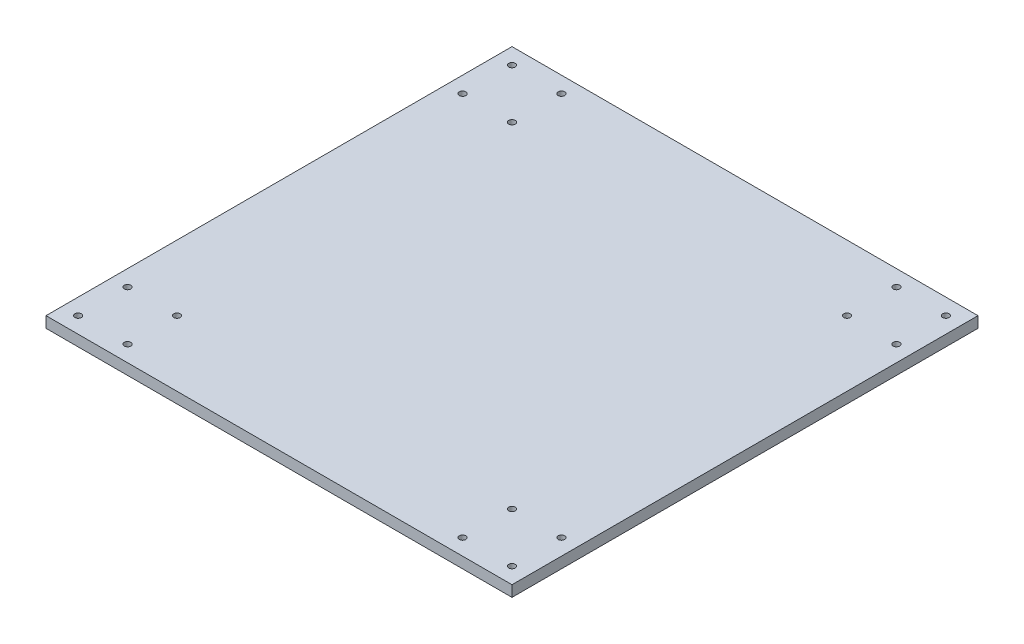
SolidWorks part; units mm, degrees
ref_plane "Front Plane" through (0, 0, 0) normal (0, 0, 1) x (1, 0, 0)
ref_plane "Top Plane" through (0, 0, 0) normal (0, 1, 0) x (1, 0, 0)
ref_plane "Right Plane" through (0, 0, 0) normal (1, 0, 0) x (0, 0, -1)
sketch "Sketch1" plane through (0, 0, 0) normal (0, 1, 0) x (1, 0, 0)
  line L0 (91.3003, -118.2497) -> (118.2497, -118.2497) construction
  line L1 (-127, -127) -> (127, -127)
  line L2 (-127, -127) -> (-127, 127)
  line L3 (-127, 127) -> (127, 127)
  line L4 (127, -127) -> (127, 127)
  line L5 (-127, -127) -> (127, 127) construction
  line L6 (-127, 127) -> (127, -127) construction
  line L7 (-104.775, 104.775) -> (104.775, 104.775) construction
  line L8 (-104.775, 104.775) -> (-104.775, -104.775) construction
  line L9 (-104.775, -104.775) -> (104.775, -104.775) construction
  line L10 (104.775, 104.775) -> (104.775, -104.775) construction
  line L11 (-104.775, 104.775) -> (104.775, -104.775) construction
  line L12 (-104.775, -104.775) -> (104.775, 104.775) construction
  line L13 (-118.2497, -118.2497) -> (-91.3003, -118.2497) construction
  line L14 (-118.2497, -118.2497) -> (-118.2497, -91.3003) construction
  line L15 (-118.2497, -91.3003) -> (-91.3003, -91.3003) construction
  line L16 (-91.3003, -118.2497) -> (-91.3003, -91.3003) construction
  line L17 (-118.2497, -118.2497) -> (-91.3003, -91.3003) construction
  line L18 (-118.2497, -91.3003) -> (-91.3003, -118.2497) construction
  line L19 (91.3003, -118.2497) -> (91.3003, -91.3003) construction
  line L20 (91.3003, -91.3003) -> (118.2497, -91.3003) construction
  line L21 (118.2497, -118.2497) -> (118.2497, -91.3003) construction
  line L22 (91.3003, -118.2497) -> (118.2497, -91.3003) construction
  line L23 (91.3003, -91.3003) -> (118.2497, -118.2497) construction
  line L24 (58.1443, -58.46) -> (85.0937, -85.4094) construction
  line L25 (91.3003, 91.3003) -> (118.2497, 91.3003) construction
  line L26 (91.3003, 91.3003) -> (91.3003, 118.2497) construction
  line L27 (91.3003, 118.2497) -> (118.2497, 118.2497) construction
  line L28 (118.2497, 91.3003) -> (118.2497, 118.2497) construction
  line L29 (91.3003, 91.3003) -> (118.2497, 118.2497) construction
  line L30 (91.3003, 118.2497) -> (118.2497, 91.3003) construction
  line L31 (-118.2497, 91.3003) -> (-91.3003, 91.3003) construction
  line L32 (-118.2497, 91.3003) -> (-118.2497, 118.2497) construction
  line L33 (-118.2497, 118.2497) -> (-91.3003, 118.2497) construction
  line L34 (-91.3003, 91.3003) -> (-91.3003, 118.2497) construction
  line L35 (-118.2497, 91.3003) -> (-91.3003, 118.2497) construction
  line L36 (-118.2497, 118.2497) -> (-91.3003, 91.3003) construction
  circle A0 centre (-118.2497, -118.2497) radius 1.778
  circle A1 centre (-91.3003, -118.2497) radius 1.778
  circle A2 centre (-118.2497, -91.3003) radius 1.778
  circle A3 centre (-91.3003, -91.3003) radius 1.778
  circle A4 centre (91.3003, -118.2497) radius 1.778
  circle A5 centre (118.2497, -118.2497) radius 1.778
  circle A6 centre (91.3003, -91.3003) radius 1.778
  circle A7 centre (118.2497, -91.3003) radius 1.778
  circle A8 centre (91.3003, 91.3003) radius 1.778
  circle A9 centre (118.2497, 91.3003) radius 1.778
  circle A10 centre (91.3003, 118.2497) radius 1.778
  circle A11 centre (118.2497, 118.2497) radius 1.778
  circle A12 centre (-118.2497, 91.3003) radius 1.778
  circle A13 centre (-91.3003, 91.3003) radius 1.778
  circle A14 centre (-118.2497, 118.2497) radius 1.778
  circle A15 centre (-91.3003, 118.2497) radius 1.778
  point P0 (0, 0)
  point P6 (0, 0)
  dimension "D1" = 22.225
extrude "Boss-Extrude1" add sketch "Sketch1" along normal blind 5.9944
